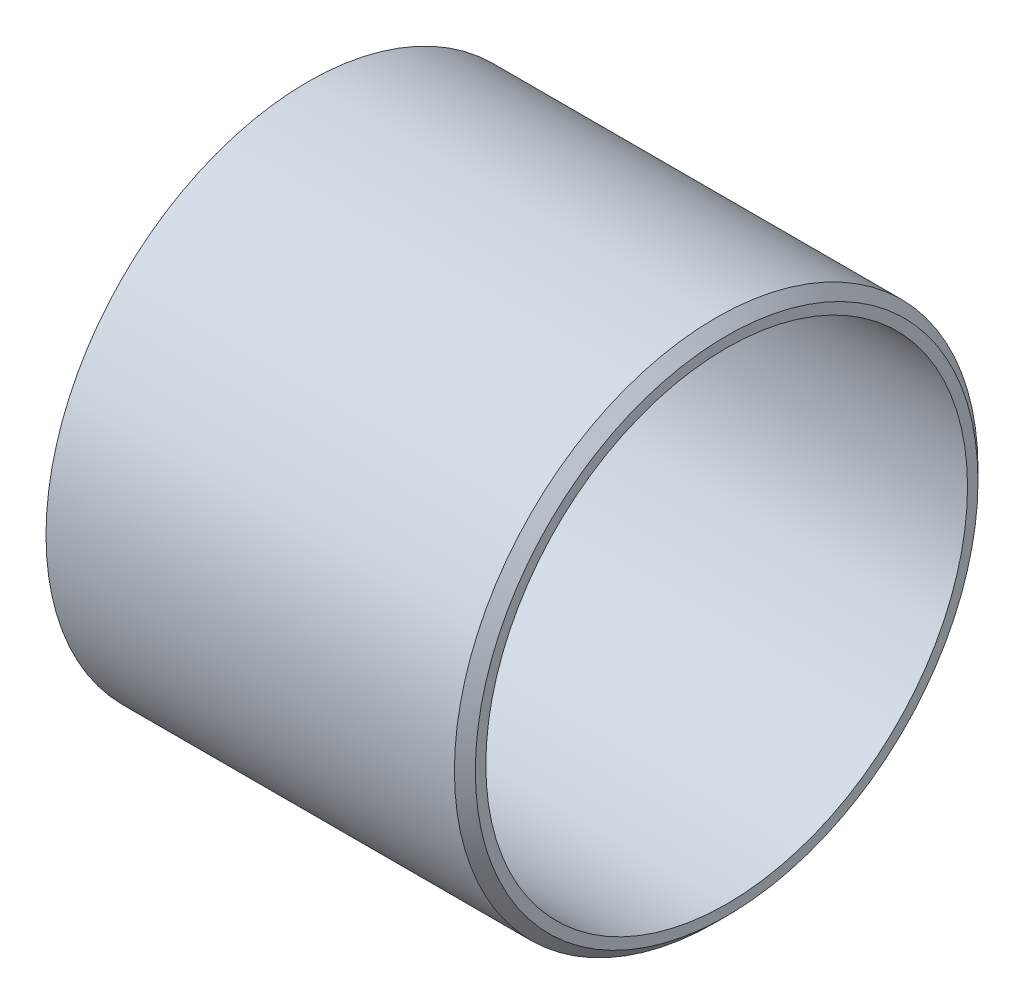
SolidWorks part; units mm, degrees
material "AISI Type 316L stainless steel"
ref_plane "Front Plane" through (0, 0, 0) normal (0, 0, 1) x (1, 0, 0)
ref_plane "Top Plane" through (0, 0, 0) normal (0, 1, 0) x (1, 0, 0)
ref_plane "Right Plane" through (0, 0, 0) normal (1, 0, 0) x (0, 0, -1)
sketch "Sketch1" plane through (0, 0, 0) normal (0, 0, 1) x (1, 0, 0)
  line L0 (20, 25) -> (-20, 25)
  line L1 (-20, 25) -> (-20, 23)
  line L2 (-20, 23) -> (20, 23)
  line L3 (20, 23) -> (20, 25)
  line L4 (0, 0) -> (15.7391, 0) construction
  line L5 (0, 0) -> (0, 23) construction
  dimension "D1" = 40
  dimension "D2" = 2
  dimension "D3" = 25
revolve "Revolve1" add sketch "Sketch1" angle 360 about L4
chamfer "Chamfer1" distance 1 angle 45 1 edges at (20, 0, 25)
